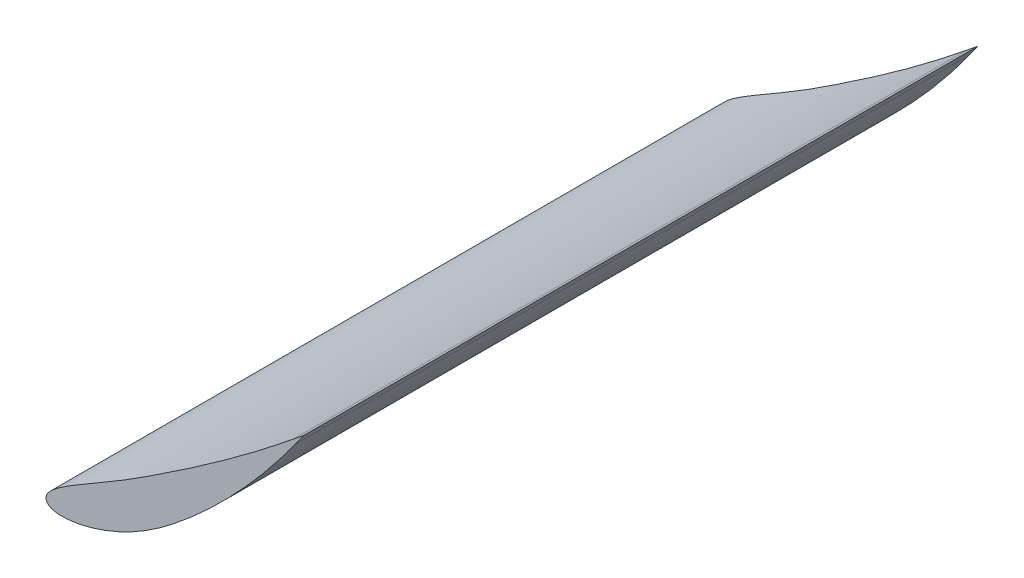
SolidWorks part; units mm, degrees
ref_plane "Front Plane" through (0, 0, 0) normal (0, 0, 1) x (1, 0, 0)
ref_plane "Top Plane" through (0, 0, 0) normal (0, 1, 0) x (1, 0, 0)
ref_plane "Right Plane" through (0, 0, 0) normal (1, 0, 0) x (0, 0, -1)
sketch "Sketch3" plane through (0, 0, 0) normal (0, 0, 1) x (1, 0, 0)
  line L7 (0, 0) -> (143.0551, 0) construction
  line L14 (0, 0) -> (-43.0922, 59.3113) construction
  line L16 (157.4681, 113.8608) -> (164.3923, 119.438)
  line L17 (164.3923, 119.438) -> (158.9109, 111.8327)
  line L19 (0, 0) -> (164.3923, 119.438) construction
  spline S1 degree 3 poles (158.9109, 111.8327) (157.6904, 110.1394) (156.4643, 108.4512) (153.986, 105.0987) (152.7362, 103.4322) (148.9547, 98.4621) (146.3914, 95.1874) (138.5749, 85.4792) (133.1965, 79.1602) (122.0982, 66.8348) (116.3789, 60.8279) (104.5681, 49.1546) (98.4773, 43.4876) (90.5921, 36.6525) (89.0003, 35.297) (85.7928, 32.6177) (84.178, 31.295) (79.3016, 27.3754) (76.0148, 24.8171) (69.2672, 19.9663) (65.8131, 17.6635) (58.7324, 13.3213) (55.1057, 11.2821) (49.5211, 8.4441) (47.6354, 7.5349) (43.8119, 5.7961) (41.8789, 4.9688) (36.0421, 2.634) (32.09, 1.2657) (26.0493, -0.4391) (24.0168, -0.949) (20.9335, -1.6066) (19.8982, -1.8079) (17.8245, -2.1674) (16.786, -2.3254) (14.7051, -2.5905) (13.6627, -2.698) (11.5728, -2.8479) (10.5255, -2.8914) (8.9493, -2.8887) (8.423, -2.8764) (7.3682, -2.8239) (6.8383, -2.7831) (5.786, -2.664) (5.2631, -2.5866) (4.2262, -2.3812) (3.7104, -2.2519) (2.7008, -1.9224) (2.2111, -1.7238) (1.5131, -1.3429) (1.2852, -1.2013) (0.8545, -0.891) (0.6511, -0.722) (0.2739, -0.3499) (0.0987, -0.1444) (-0.2033, 0.2919) (-0.3318, 0.5231) (-0.5417, 1.0127) (-0.6216, 1.2695) (-0.7222, 1.7876) (-0.743, 2.0534) (-0.7291, 2.5882) (-0.6953, 2.8507) (-0.5852, 3.3679) (-0.5082, 3.6242) (-0.2261, 4.3716) (0.0271, 4.834) (0.6057, 5.7193) (0.9308, 6.1423) (1.6141, 6.9417) (1.974, 7.3223) (3.088, 8.4278) (3.8783, 9.1147) (5.5055, 10.4393) (6.3454, 11.0752) (8.8932, 12.925) (10.6365, 14.0857) (14.1608, 16.3459) (15.943, 17.4435) (19.5261, 19.6084) (21.3275, 20.675) (26.7439, 23.8548) (30.3704, 25.9494) (37.6072, 30.165) (41.2176, 32.2844) (48.3955, 36.5864) (51.9631, 38.7686) (57.2702, 42.107) (59.0318, 43.2307) (62.5378, 45.5032) (64.2828, 46.6512) (69.5156, 50.0984) (73.0036, 52.3972) (83.4387, 59.3364) (90.3627, 64.0104) (104.1029, 73.5165) (110.9192, 78.3484) (124.427, 88.1951) (131.1192, 93.2089) (141.0665, 100.8629) (144.368, 103.4363) (149.2969, 107.3248) (150.936, 108.6259) (154.2071, 111.2369) (155.8382, 112.548) (157.4681, 113.8608) knots 0 0 0 0 0.015625 0.015625 0.03125 0.03125 0.0625 0.0625 0.125 0.125 0.1875 0.1875 0.25 0.25 0.265625 0.265625 0.28125 0.28125 0.3125 0.3125 0.34375 0.34375 0.375 0.375 0.390625 0.390625 0.40625 0.40625 0.4375 0.4375 0.453125 0.453125 0.460937 0.460937 0.46875 0.46875 0.476562 0.476562 0.484375 0.484375 0.488281 0.488281 0.492187 0.492187 0.496094 0.496094 0.5 0.5 0.503906 0.503906 0.505859 0.505859 0.507812 0.507812 0.509766 0.509766 0.511719 0.511719 0.513672 0.513672 0.515625 0.515625 0.517578 0.517578 0.519531 0.519531 0.523437 0.523437 0.527344 0.527344 0.53125 0.53125 0.539062 0.539062 0.546875 0.546875 0.5625 0.5625 0.578125 0.578125 0.59375 0.59375 0.625 0.625 0.65625 0.65625 0.6875 0.6875 0.703125 0.703125 0.71875 0.71875 0.75 0.75 0.8125 0.8125 0.875 0.875 0.9375 0.9375 0.96875 0.96875 0.984375 0.984375 1 1 1 1
  dimension "D1" = 126
  dimension "D2" = 203.2
extrude "Boss-Extrude3" add sketch "Sketch3" along normal blind 431.8
sketch "Sketch4" plane through (0, 0, 0) normal (0, 0, -1) x (-1, 0, 0)
  line L0 (0, 0) -> (-164.3923, 119.438) construction
sketch "Sketch5" plane through (0, 0, 431.8) normal (0, 0, 1) x (1, 0, 0)
  line L0 (0, 0) -> (164.3923, 119.438) construction
sketch3d "3DSketch1"
  line L0 (0, 0, 0) -> (0, 0, 431.8)
